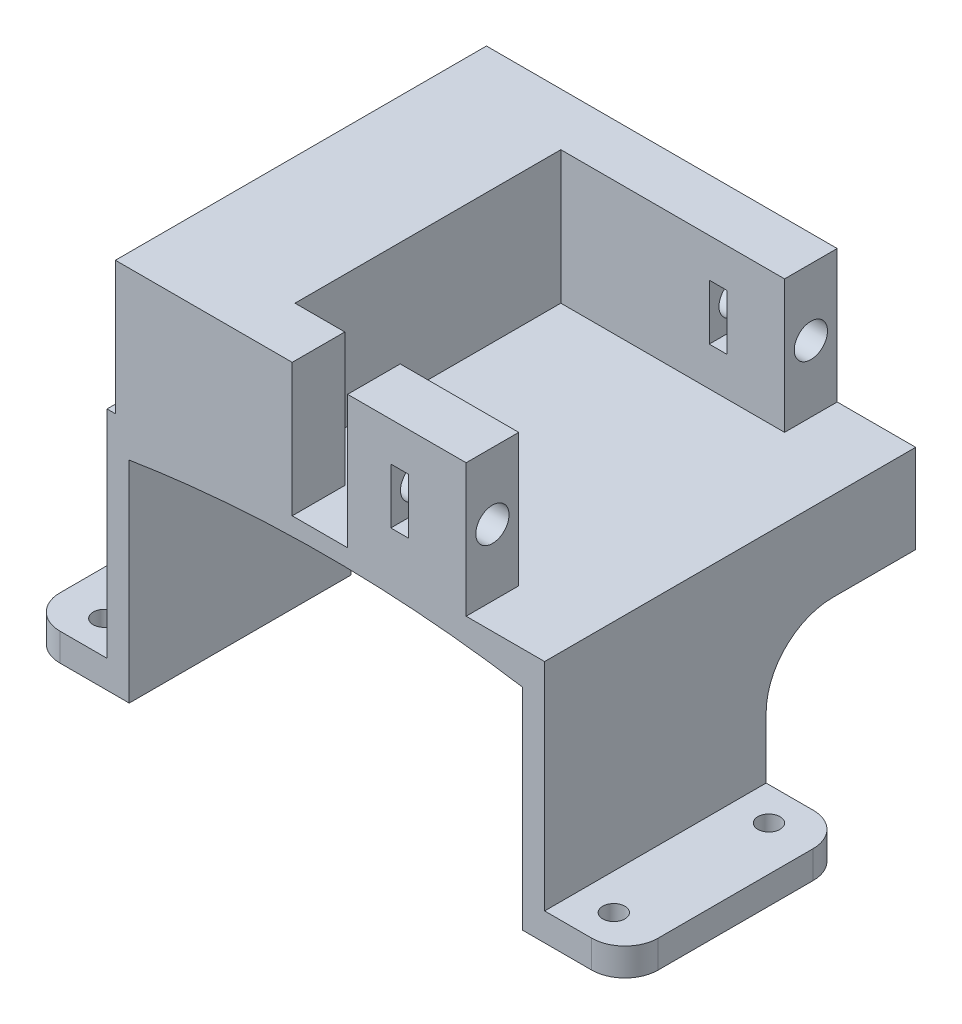
SolidWorks part; units mm, degrees
ref_plane "Front Plane" through (0, 0, 0) normal (0, 0, 1) x (1, 0, 0)
ref_plane "Top Plane" through (0, 0, 0) normal (0, 1, 0) x (1, 0, 0)
ref_plane "Right Plane" through (0, 0, 0) normal (1, 0, 0) x (0, 0, -1)
sketch "Sketch1" plane through (0, 0, 0) normal (0, 0, 1) x (1, 0, 0)
  line L0 (17, -20) -> (19, -20)
  line L1 (-19, -20) -> (-17, -20)
  line L2 (-19, -20) -> (-19, 14)
  line L3 (-19, 14) -> (19, 14)
  line L4 (19, -20) -> (19, 14)
  line L8 (-17, -20) -> (-17, -1)
  line L9 (-17, -1) -> (17, -1)
  line L10 (17, -20) -> (17, -1)
  dimension "D3" = 19
extrude "Boss-Extrude1" add sketch "Sketch1" along normal blind 33.5
sketch "Sketch2" plane through (19, 0, 0) normal (1, 0, 0) x (0, 0, -1)
  line L1 (-33.5, -20) -> (0, -20) construction
  line L3 (-33.5, -20) -> (-33.5, -17.5)
  line L4 (-33.5, -17.5) -> (-13.5, -17.5)
  line L5 (-13.5, -20) -> (-13.5, -17.5)
  line L9 (-33.5, -20) -> (-13.5, -20)
  point P0 (-16.75, -20)
  dimension "D1" = 2.5
extrude "Boss-Extrude2" add sketch "Sketch2" along normal blind 8
sketch "Sketch9" plane through (0, -17.5, 0) normal (0, 1, 0) x (1, 0, 0)
  line L0 (27, -13.5) -> (19, -13.5) construction
  circle A0 centre (23, -16.5) radius 1
  circle A1 centre (23, -30.5) radius 1
  dimension "D1" = 14
  dimension "D2" = 3
ref_plane "Plane1" through (0, 0, 16.75) normal (0, 0, 1) x (1, 0, 0)
ref_plane "Plane2" through (0, 0, 0) normal (1, 0, 0) x (0, 0, -1)
sketch "Sketch12" plane through (0, 14, 0) normal (0, 1, 0) x (1, 0, 0)
  line L0 (-7.5359, -4.75) -> (-7.5359, -28.75)
  line L1 (12.6641, -4.75) -> (-7.5359, -4.75)
  line L3 (12.6641, 0) -> (19, 0)
  line L5 (12.6641, 0) -> (12.6641, -4.75)
  line L6 (12.6641, -33.5) -> (19, -33.5)
  line L7 (19, 0) -> (19, -33.5)
  line L8 (12.6641, -28.75) -> (12.6641, -33.5)
  line L10 (-3.0359, -28.75) -> (-3.0359, -33.5)
  line L11 (-3.0359, -33.5) -> (1.9641, -33.5)
  line L12 (1.9641, -28.75) -> (1.9641, -33.5)
  line L13 (-7.5359, -28.75) -> (-3.0359, -28.75)
  line L14 (1.9641, -28.75) -> (12.6641, -28.75)
extrude "Cut-Extrude5" cut sketch "Sketch12" against normal blind 12
sketch "Esboço10" plane through (19, 0, 0) normal (1, 0, 0) x (0, 0, -1)
  line L1 (-33.5, 2) -> (0, 2)
  line L2 (-33.5, 2) -> (-33.5, -17.5)
  line L3 (-33.5, -17.5) -> (-13.5, -17.5)
  line L4 (0, 2) -> (0, -17.5)
  line L7 (-13.5, -17.5) -> (-13.5, -20)
  line L8 (-13.5, -20) -> (0, -20)
  line L9 (0, -17.5) -> (0, -20)
extrude "Ressalto-extrusão4" add sketch "Esboço10" along normal blind 0.75
sketch "Sketch6" plane through (12.6641, 0, 0) normal (1, 0, 0) x (0, 0, -1)
  line L0 (-31.125, 14) -> (-31.125, 2) construction
  line L1 (-28.75, 14) -> (-33.5, 14) construction
  line L2 (-28.75, 2) -> (-33.5, 2) construction
  circle A2 centre (-31.125, 8) radius 1.5
  dimension "D1" = 6
extrude "Cut-Extrude6" cut sketch "Sketch6" against normal blind 12
sketch "Sketch14" plane through (0, 0, 33.5) normal (0, 0, 1) x (1, 0, 0)
  line L0 (12.6641, 2) -> (-19, 2) construction
  line L1 (-19, 14) -> (-19, -20) construction
  line L2 (12.6641, 8) -> (-19, 8) construction
  line L3 (12.6641, 2) -> (12.6641, 14) construction
  line L4 (6.6641, 2) -> (6.6641, 8) construction
  line L6 (5.8641, 5.5) -> (7.4641, 5.5)
  line L7 (5.8641, 5.5) -> (5.8641, 10.5)
  line L8 (5.8641, 10.5) -> (7.4641, 10.5)
  line L9 (7.4641, 5.5) -> (7.4641, 10.5)
  line L10 (5.8641, 5.5) -> (7.4641, 10.5) construction
  line L11 (5.8641, 10.5) -> (7.4641, 5.5) construction
  dimension "D1" = 6
  dimension "D2" = 1.6
  dimension "D3" = 5
extrude "Cut-Extrude8" cut sketch "Sketch14" against normal up to next contours L7 L8 L9 L6
mirror "Mirror6" about plane through (0, 0, 16.75) normal (0, 0, 1) of "Cut-Extrude8", "Cut-Extrude6"
extrude "Corte-extrusão1" cut sketch "Sketch9" against normal through all
fillet "Filete1" radius 3 2 edges at (27, -18.75, 13.5) (27, -18.75, 33.5)
sketch "Esboço6" plane through (-19, 0, 0) normal (-1, 0, 0) x (0, 0, 1)
  line L0 (33.5, 14) -> (0, 14) construction
  line L1 (33.5, 14) -> (33.5, -20) construction
  circle A0 centre (22.25, 8) radius 1
  dimension "D2" = 11.25
  dimension "D3" = 2
  dimension "D1" = 6
extrude "Corte-extrusão6" cut sketch "Esboço6" against normal blind 2
sketch "Esboço8" plane through (0, 0, 33.5) normal (0, 0, 1) x (1, 0, 0)
  line L0 (17, -20) -> (24, -20) construction
  line L1 (17, -1) -> (17.75, -1)
  line L2 (17, -1) -> (17, -20)
  line L3 (17, -20) -> (17.75, -20)
  line L4 (17.75, -1) -> (17.75, -20)
  line L6 (-17, -1) -> (-17.75, -1)
  line L7 (-17, -1) -> (-17, -15)
  line L8 (-17, -15) -> (-17.75, -15)
  line L9 (-17.75, -1) -> (-17.75, -15)
  dimension "D1" = 0.75
  dimension "D2" = 0.75
extrude "Corte-extrusão8" cut sketch "Esboço8" against normal through all
mirror "Espelhar1" about plane through (0, 0, 0) normal (1, 0, 0) of "Corte-extrusão8", "Filete1", "Corte-extrusão1", "Boss-Extrude2", "Ressalto-extrusão4"
sketch "Esboço11" plane through (0, 0, 33.5) normal (0, 0, 1) x (1, 0, 0)
  line L0 (0, -12.1) -> (0, 12.1) construction
  line L1 (-17.75, -1) -> (17.75, -1)
  spline S0 degree 2 poles (-17.75, -1) (0, 1.8385) (17.75, -1) knots 0 0 0 1 1 1
extrude "Corte-extrusão9" cut sketch "Esboço11" against normal through all
sketch "Esboço12" plane through (19.75, 0, 0) normal (1, 0, 0) x (0, 0, -1)
  line L1 (0, -20) -> (-13.5, -20)
  line L2 (0, -20) -> (0, -6)
  line L3 (0, -6) -> (-7.5, -6)
  line L4 (-13.5, -20) -> (-13.5, -12)
  arc A0 (-7.5, -6) -> (-13.5, -12) centre (-7.5, -12) ccw
  point P7 (-13.5, -6)
  dimension "D3" = 6
  dimension "D1" = 13.5
  dimension "D2" = 14
extrude "Corte-extrusão10" cut sketch "Esboço12" against normal through all
